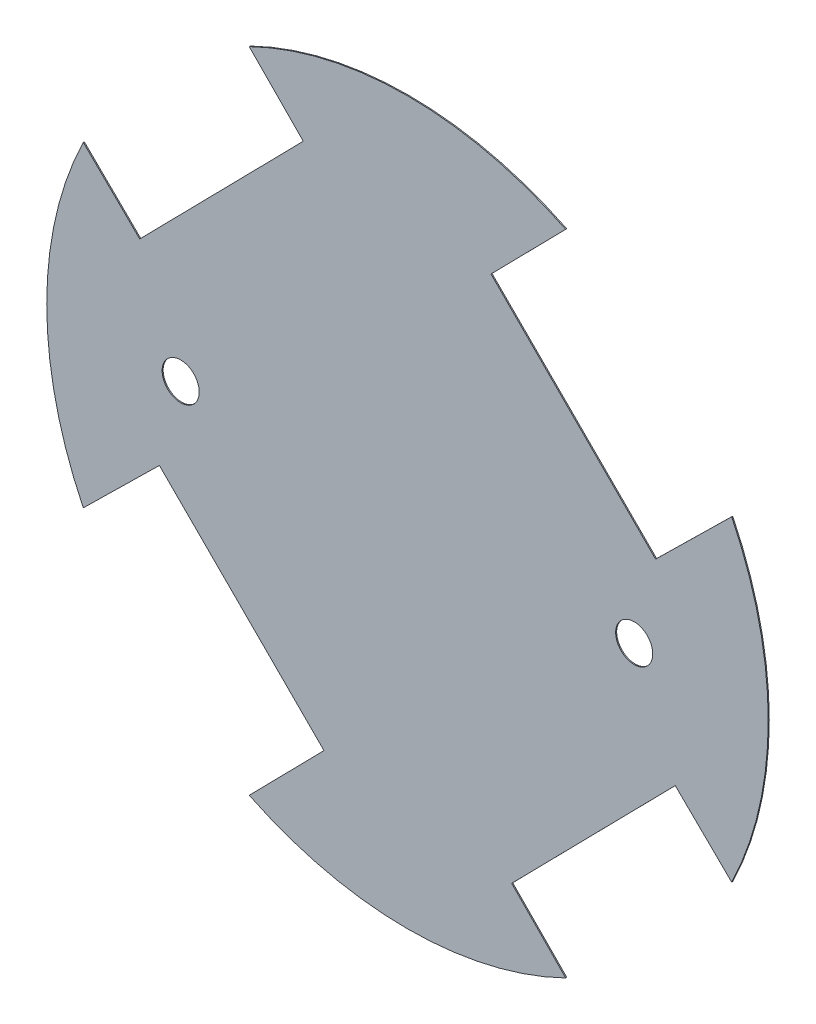
SolidWorks part; units mm, degrees
ref_plane "Front Plane" through (0, 0, 0) normal (0, 0, 1) x (1, 0, 0)
ref_plane "Top Plane" through (0, 0, 0) normal (0, 1, 0) x (1, 0, 0)
ref_plane "Right Plane" through (0, 0, 0) normal (1, 0, 0) x (0, 0, -1)
sketch "Sketch2" plane through (0, 0, 0) normal (0, 0, 1) x (1, 0, 0)
  line L0 (767.9479, -1572.6258) -> (505.9065, -1305.9815)
  line L1 (505.9065, -1305.9815) -> (1299.2113, -498.7421)
  line L2 (1299.2113, -498.7421) -> (1572.8835, -767.6902)
  line L3 (1572.8835, 767.6902) -> (1203.8296, 405.0068)
  line L4 (1203.8296, 405.0068) -> (405.2646, 1203.5718)
  line L5 (405.2646, 1203.5718) -> (767.9479, 1572.6258)
  line L6 (-767.4324, 1572.6258) -> (-505.391, 1305.9815)
  line L7 (-505.391, 1305.9815) -> (-1298.6958, 498.7421)
  line L8 (-1298.6958, 498.7421) -> (-1572.368, 767.6902)
  line L9 (-1572.368, -767.6902) -> (-1203.3141, -405.0068)
  line L10 (-1203.3141, -405.0068) -> (-404.7491, -1203.5718)
  line L11 (-404.7491, -1203.5718) -> (-767.4324, -1572.6258)
  arc A0 (-767.4324, -1572.6258) -> (767.9479, -1572.6258) centre (0.2578, 0) ccw
  arc A1 (1572.8835, -767.6902) -> (1572.8835, 767.6902) centre (0.2578, 0) ccw
  arc A2 (767.9479, 1572.6258) -> (-767.4324, 1572.6258) centre (0.2578, 0) ccw
  arc A3 (-1572.368, 767.6902) -> (-1572.368, -767.6902) centre (0.2578, 0) ccw
  circle A4 centre (-1090, 0) radius 90
  circle A5 centre (1090, 0) radius 90
  dimension "D1" = 2
extrude "Boss-Extrude1" add sketch "Sketch2" along normal blind 5 contours L0 L1 L2 A1 L3 L4 L5 A2 L6 L7 L8 A3 L9 L10 L11 A0
sketch "Sketch3" plane through (0, 0, 0) normal (0, 0, 1) x (1, 0, 0)
  circle A0 centre (-1100, 0) radius 90
  circle A2 centre (1100, 0) radius 90
  dimension "D1" = 2
extrude "Cut-Extrude3" cut sketch "Sketch3" along normal blind 10
